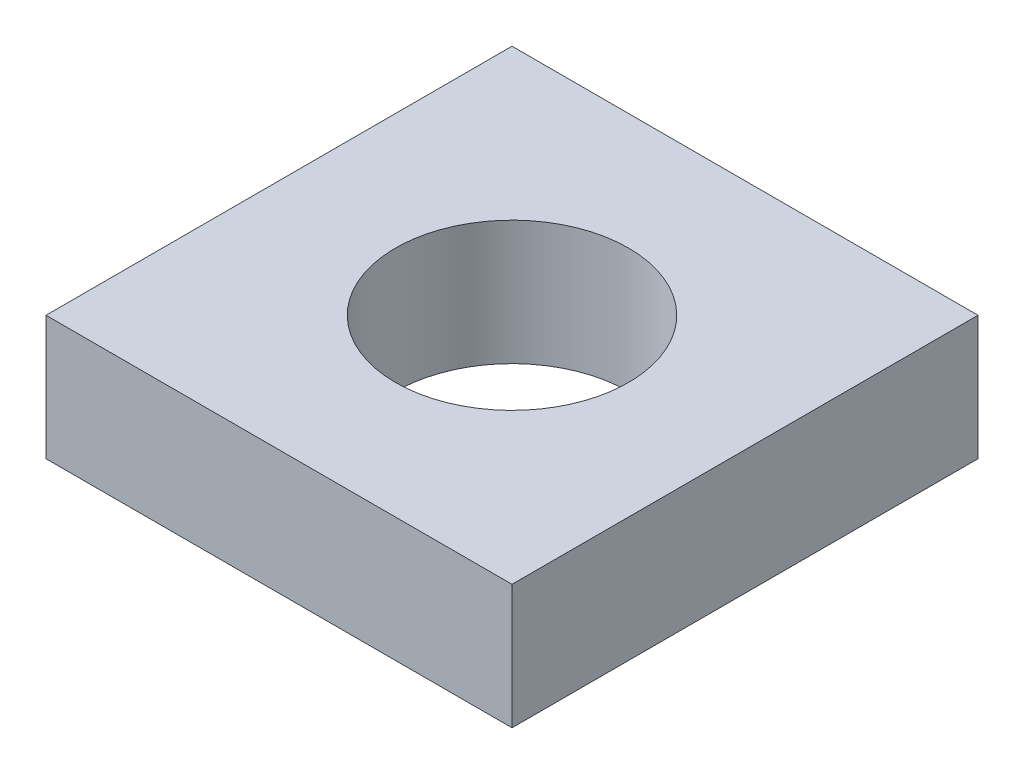
SolidWorks part; units mm, degrees
ref_plane "Front Plane" through (0, 0, 0) normal (0, 0, 1) x (1, 0, 0)
ref_plane "Top Plane" through (0, 0, 0) normal (0, 1, 0) x (1, 0, 0)
ref_plane "Right Plane" through (0, 0, 0) normal (1, 0, 0) x (0, 0, -1)
sketch "Sketch1" plane through (0, 0, 0) normal (0, 1, 0) x (1, 0, 0)
  line L1 (-3, 3) -> (3, 3)
  line L2 (-3, 3) -> (-3, -3)
  line L3 (-3, -3) -> (3, -3)
  line L4 (3, 3) -> (3, -3)
  line L5 (-3, 3) -> (3, -3) construction
  line L6 (-3, -3) -> (3, 3) construction
  circle A0 centre (0, 0) radius 1.5
  point P0 (0, 0)
  dimension "D3" = 3
  dimension "D1" = 6
  dimension "D2" = 6
extrude "Boss-Extrude1" add sketch "Sketch1" along normal blind 1.6
